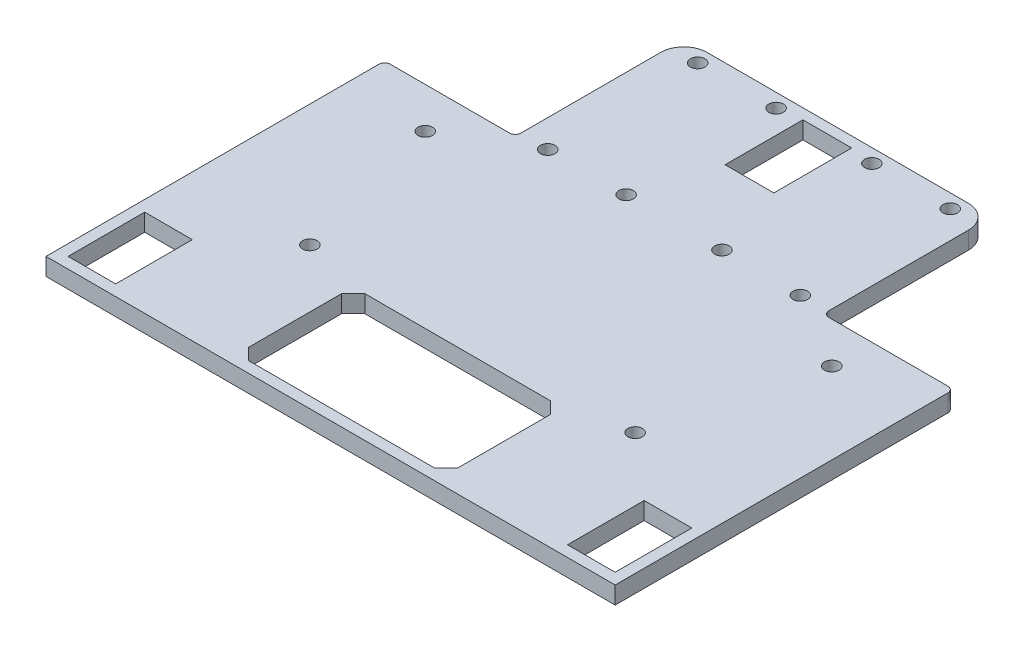
SolidWorks part; units mm, degrees
ref_plane "Спереди" through (0, 0, 0) normal (0, 0, 1) x (1, 0, 0)
ref_plane "Сверху" through (0, 0, 0) normal (0, 1, 0) x (1, 0, 0)
ref_plane "Справа" through (0, 0, 0) normal (1, 0, 0) x (0, 0, -1)
sketch "Эскиз1" plane through (0, 0, 0) normal (0, 1, 0) x (1, 0, 0)
  line L0 (0, 0) -> (0, 98) construction
  line L2 (-49, 10.6718) -> (-49, 67.9663)
  line L3 (-22.5, 98) -> (22.5, 98)
  line L4 (49, 10.6718) -> (49, 67.9663)
  line L11 (-48, 68.9663) -> (-27.5, 68.9663)
  line L14 (48, 68.9663) -> (27.5, 68.9663)
  line L22 (-47.1, 25.7676) -> (-47.1, 12.5676)
  line L27 (-47.1, 12.5676) -> (-38.9, 12.5676)
  line L28 (-38.9, 25.7676) -> (-38.9, 12.5676)
  line L29 (-47.1, 25.7676) -> (-38.9, 25.7676)
  line L30 (38.9, 25.7676) -> (38.9, 12.5676)
  line L35 (38.9, 12.5676) -> (47.1, 12.5676)
  line L36 (47.1, 25.7676) -> (47.1, 12.5676)
  line L37 (38.9, 25.7676) -> (47.1, 25.7676)
  line L38 (-26.5, 94) -> (-26.5, 69.9663)
  line L39 (26.5, 94) -> (26.5, 69.9663)
  line L40 (-26.5, 81.7332) -> (26.5, 81.7332) construction
  line L41 (0, 98) -> (0, 96) construction
  line L42 (-4.2, 96.2) -> (4.2, 96.2)
  line L47 (4.2, 96.2) -> (4.2, 82.8)
  line L48 (-4.2, 82.8) -> (4.2, 82.8)
  line L49 (-4.2, 96.2) -> (-4.2, 82.8)
  line L50 (16, 12.5676) -> (-16, 12.5676)
  line L51 (-16, 12.5676) -> (-18, 14.5676)
  line L52 (-18, 14.5676) -> (-18, 30.5676)
  line L53 (-18, 30.5676) -> (-16, 32.5676)
  line L54 (-16, 32.5676) -> (16, 32.5676)
  line L55 (16, 12.5676) -> (18, 14.5676)
  line L56 (18, 14.5676) -> (18, 30.5676)
  line L57 (18, 30.5676) -> (16, 32.5676)
  line L58 (-49, 10.6718) -> (49, 10.6718)
  arc A0 (49, 67.9663) -> (48, 68.9663) centre (48, 67.9663) ccw
  arc A5 (-49, 67.9663) -> (-48, 68.9663) centre (-48, 67.9663) cw
  circle A10 centre (-21.75, 95.6244) radius 1.25
  circle A11 centre (-8.25, 95.6244) radius 1.25
  circle A12 centre (8.25, 95.6244) radius 1.25
  circle A13 centre (21.75, 95.6244) radius 1.25
  circle A14 centre (21.75, 69.8083) radius 1.25
  circle A15 centre (8.25, 69.8083) radius 1.25
  circle A16 centre (-8.25, 69.8083) radius 1.25
  circle A17 centre (-21.75, 69.8083) radius 1.25
  arc A19 (-26.5, 69.9663) -> (-27.5, 68.9663) centre (-27.5, 69.9663) cw
  arc A21 (26.5, 69.9663) -> (27.5, 68.9663) centre (27.5, 69.9663) ccw
  circle A22 centre (-35, 61.9663) radius 1.25
  circle A23 centre (-28, 35.111) radius 1.25
  circle A24 centre (28, 35.111) radius 1.25
  circle A25 centre (35, 61.9663) radius 1.25
  arc A26 (-22.5, 98) -> (-26.5, 94) centre (-22.5, 94) ccw
  arc A27 (22.5, 98) -> (26.5, 94) centre (22.5, 94) cw
  point P13 (-27, 99)
  point P14 (-27, 68.9663)
  point P22 (49, 68.9663)
  point P25 (27, 68.9663)
  point P28 (49, 94.5)
  point P31 (49, 98)
  point P34 (27, 94.5)
  point P37 (-49, 68.9663)
  point P46 (-49, 94.5)
  point P49 (-49, 98)
  point P107 (0, 12.5676)
  point P110 (0, 32.5676)
  dimension "D3" = 1
  dimension "D2" = 4
  dimension "D1" = 3.5
  dimension "D6" = 2
  dimension "D7" = 16
  dimension "D8" = 2
  dimension "D9" = 2
  dimension "D10" = 16
  dimension "D11" = 2
  dimension "D12" = 2
extrude "Бобышка-Вытянуть1" add sketch "Эскиз1" along normal blind 3
